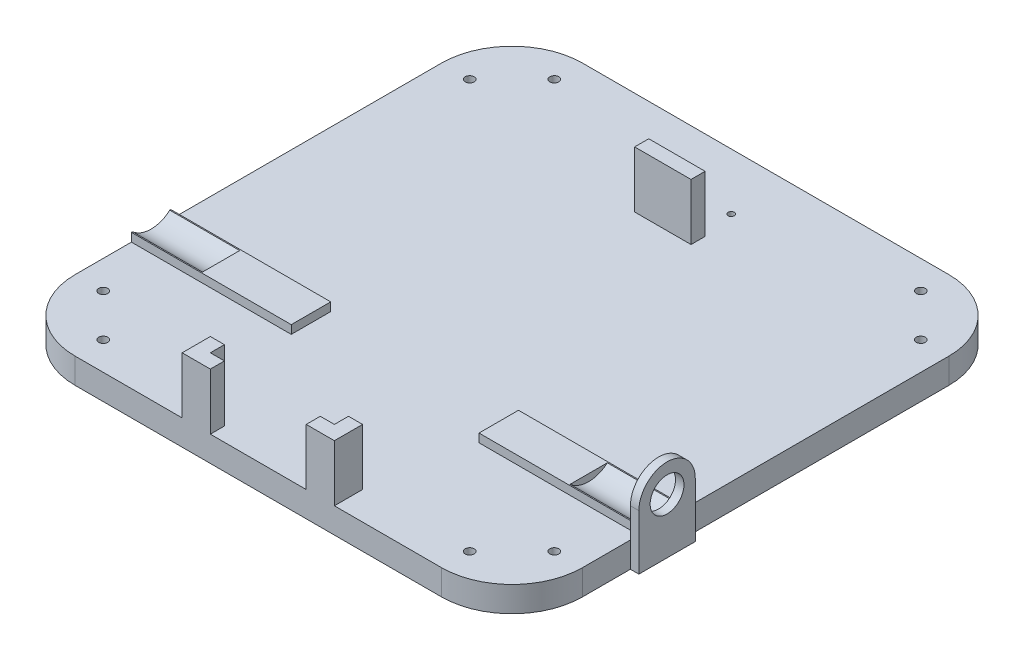
SolidWorks part; units mm, degrees
ref_plane "Front Plane" through (0, 0, 0) normal (0, 0, 1) x (1, 0, 0)
ref_plane "Top Plane" through (0, 0, 0) normal (0, 1, 0) x (1, 0, 0)
ref_plane "Right Plane" through (0, 0, 0) normal (1, 0, 0) x (0, 0, -1)
sketch "Sketch1" plane through (0, 0, 0) normal (0, 1, 0) x (1, 0, 0)
  line L1 (-65, -90) -> (65, -90)
  line L2 (-90, -65) -> (-90, 65)
  line L3 (-65, 90) -> (65, 90)
  line L4 (90, -65) -> (90, 65)
  arc A0 (-90, 65) -> (-65, 90) centre (-65, 65) cw
  arc A1 (65, 90) -> (90, 65) centre (65, 65) cw
  arc A2 (90, -65) -> (65, -90) centre (65, -65) cw
  arc A3 (-65, -90) -> (-90, -65) centre (-65, -65) cw
  point P4 (-90, 0)
  point P6 (0, 90)
  dimension "D3" = 25
  dimension "D1" = 180
  dimension "D2" = 180
extrude "Plate" add sketch "Sketch1" along normal blind 9
sketch "Sketch2" plane through (0, 9, 0) normal (0, 1, 0) x (1, 0, 0)
  line L0 (-7.747, 70) -> (7.747, 70) construction
  line L1 (0, 90) -> (0, 70) construction
  line L2 (-65, 90) -> (65, 90) construction
  circle A1 centre (-7.747, 70) radius 1.09
  circle A2 centre (7.747, 70) radius 1.09
  dimension "D3" = 2.18
  dimension "D1" = 15.494
  dimension "D2" = 20
extrude "Caster Holes" cut sketch "Sketch2" against normal through all
sketch "Sketch3" plane through (0, 9, 0) normal (0, 1, 0) x (1, 0, 0)
  line L0 (-65, 90) -> (-65, -90) construction
  line L1 (65, 90) -> (65, -90) construction
  line L2 (-90, 65) -> (90, 65) construction
  line L3 (-90, -65) -> (90, -65) construction
  circle A0 centre (-65, 80) radius 1.6
  circle A1 centre (-80, 65) radius 1.6
  circle A2 centre (80, 65) radius 1.6
  circle A3 centre (80, -65) radius 1.6
  circle A4 centre (65, 80) radius 1.6
  circle A5 centre (65, -80) radius 1.6
  circle A6 centre (-65, -80) radius 1.6
  circle A7 centre (-80, -65) radius 1.6
  dimension "D1" = 3.2
  dimension "D2" = 15
  dimension "D3" = 15
  dimension "D4" = 15
  dimension "D5" = 15
  dimension "D6" = 15
  dimension "D7" = 15
  dimension "D8" = 15
  dimension "D9" = 15
extrude "Hex Holes" cut sketch "Sketch3" against normal through all
sketch "Sketch4" plane through (0, 9, 0) normal (0, 1, 0) x (1, 0, 0)
  line L0 (-27, -90) -> (-27, -80)
  line L1 (-65, -90) -> (65, -90) construction
  line L2 (-27, -80) -> (-22, -80)
  line L3 (-22, -80) -> (-22, -85)
  line L4 (-22, -85) -> (-17, -85)
  line L5 (-17, -85) -> (-17, -90)
  line L6 (-17, -90) -> (-27, -90)
  line L7 (17, -90) -> (17, -85)
  line L8 (17, -85) -> (22, -85)
  line L9 (22, -85) -> (22, -80)
  line L10 (22, -80) -> (27, -80)
  line L11 (27, -80) -> (27, -90)
  line L12 (27, -90) -> (17, -90)
  line L13 (-10, 58.5) -> (10, 58.5)
  line L14 (10, 58.5) -> (10, 53.5)
  line L15 (10, 53.5) -> (-10, 53.5)
  line L16 (-10, 53.5) -> (-10, 58.5)
  line L17 (-90, -65) -> (-90, 65) construction
  point P20 (0, 53.5)
  dimension "D1" = 5
  dimension "D2" = 44
  dimension "D3" = 63
  dimension "D4" = 20
  dimension "D5" = 5
  dimension "D6" = 138.5
extrude "Boss-Extrude1" add sketch "Sketch4" along normal blind 20
sketch "Sketch5" plane through (0, 9, 0) normal (0, 1, 0) x (1, 0, 0)
  line L0 (-90, -65) -> (-90, 65) construction
  line L1 (-90, -45) -> (-33.3, -45)
  line L2 (-90, -45) -> (-90, -31)
  line L3 (-90, -31) -> (-33.3, -31)
  line L4 (-33.3, -45) -> (-33.3, -31)
  line L5 (90, -65) -> (90, 65) construction
  line L6 (90, -45) -> (33.3, -45)
  line L7 (90, -45) -> (90, -31)
  line L8 (90, -31) -> (33.3, -31)
  line L9 (33.3, -45) -> (33.3, -31)
  line L10 (-65, -90) -> (65, -90) construction
  dimension "D1" = 14
  dimension "D2" = 45
  dimension "D3" = 56.7
extrude "Boss-Extrude2" add sketch "Sketch5" along normal blind 3
sketch "Sketch6" plane through (-90, 0, 0) normal (-1, 0, 0) x (0, 0, 1)
  line L0 (31, 12) -> (45, 12) construction
  line L1 (45, 9) -> (65, 9) construction
  circle A0 centre (38, 19.5) radius 10
  point P5 (38, 12)
  dimension "D1" = 20
  dimension "D2" = 10.5
extrude "Cut-Extrude1" cut sketch "Sketch6" against normal blind 24.8
sketch "Sketch7" plane through (90, 0, 0) normal (1, 0, 0) x (0, 0, -1)
  line L0 (-31, 9) -> (65, 9) construction
  line L1 (-45, 12) -> (-31, 12) construction
  circle A0 centre (-38, 19.5) radius 10
  point P6 (-38, 12)
  dimension "D1" = 20
  dimension "D2" = 10.5
extrude "Cut-Extrude2" cut sketch "Sketch7" against normal blind 24.8
sketch "Sketch8" plane through (90, 0, 0) normal (1, 0, 0) x (0, 0, -1)
  line L0 (-48, 19.5) -> (-48, 0)
  line L1 (-65, 0) -> (65, 0) construction
  line L2 (-48, 0) -> (-28, 0)
  line L3 (-28, 19.5) -> (-28, 0)
  arc A2 (-28, 19.5) -> (-48, 19.5) centre (-38, 19.5) ccw
  circle A3 centre (-38, 19.5) radius 6
  point P9 (-48, 0)
  dimension "D1" = 12
  dimension "D2" = 10
  dimension "D3" = 20
extrude "Boss-Extrude4" add sketch "Sketch8" along normal blind 3
